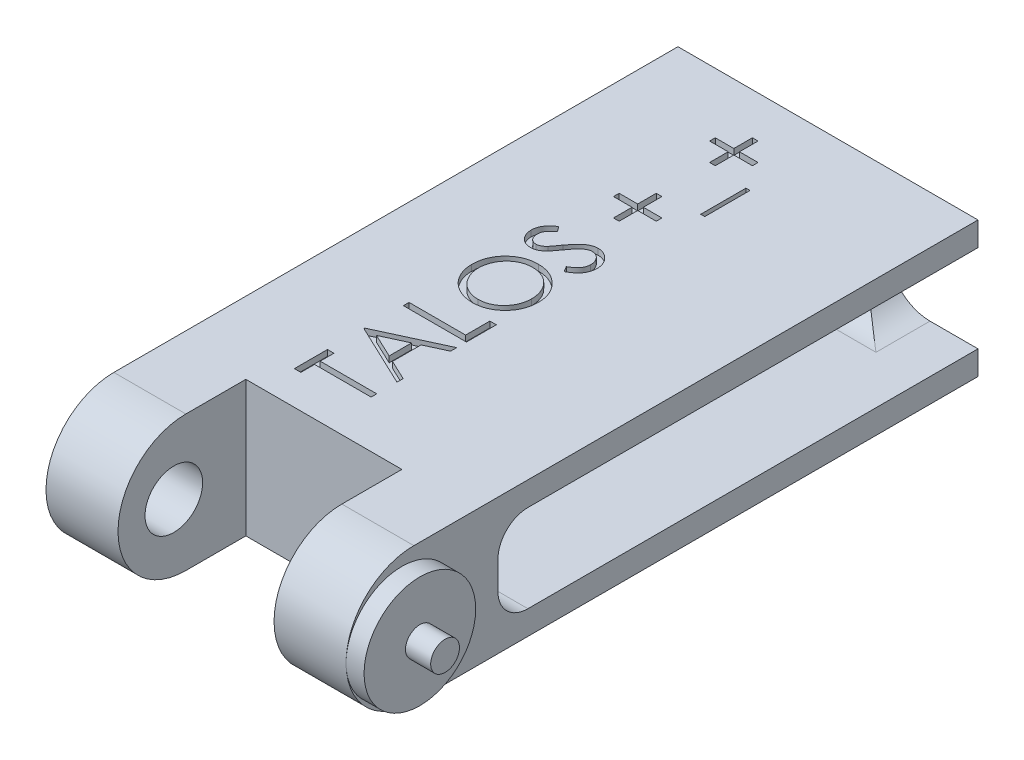
SolidWorks part; units mm, degrees
ref_plane "Front Plane" through (0, 0, 0) normal (0, 0, 1) x (1, 0, 0)
ref_plane "Top Plane" through (0, 0, 0) normal (0, 1, 0) x (1, 0, 0)
ref_plane "Right Plane" through (0, 0, 0) normal (1, 0, 0) x (0, 0, -1)
sketch "Sketch1" plane through (0, 0, 0) normal (0, 0, 1) x (1, 0, 0)
  line L1 (-10, 7.3) -> (10, 7.3)
  line L2 (-10, 7.3) -> (-10, -7.3)
  line L3 (-10, -7.3) -> (10, -7.3)
  line L4 (10, 7.3) -> (10, -7.3)
  line L5 (0, -7.3) -> (0, 7.3) construction
  line L6 (-10, 0) -> (10, 0) construction
  circle A0 centre (-6, 0) radius 1.65
  circle A1 centre (6, 0) radius 1.65
  point P0 (0, 0)
  dimension "D3" = 3.3
  dimension "D4" = 12
  dimension "D1" = 20
  dimension "D2" = 14.6
extrude "Boss-Extrude1" add sketch "Sketch1" along normal blind 4
sketch "Sketch2" plane through (0, -7.3, 0) normal (0, -1, 0) x (1, 0, 0)
  line L0 (-10, 0) -> (10, 0) construction
  line L1 (-25, 0) -> (25, 0)
  line L2 (-25, 0) -> (-25, 80)
  line L3 (-25, 80) -> (25, 80)
  line L4 (25, 0) -> (25, 80)
  point P4 (0, 80)
  point P6 (25, 6.4269)
  dimension "D1" = 50
  dimension "D2" = 80
extrude "Boss-Extrude2" add sketch "Sketch2" along normal blind 4
chamfer "Chamfer1" [suppressed] distance 10 angle 45
mirror "Mirror1" about plane through (0, 0, 0) normal (0, 1, 0) of "Boss-Extrude2"
sketch "Sketch3" plane through (0, 0, 80) normal (0, 0, 1) x (1, 0, 0)
  line L1 (-25, 11.3) -> (25, 11.3)
  line L2 (-25, 11.3) -> (-25, -11.3)
  line L3 (-25, -11.3) -> (25, -11.3)
  line L4 (25, 11.3) -> (25, -11.3)
extrude "Boss-Extrude3" add sketch "Sketch3" along normal blind 4
sketch "Sketch4" plane through (25, 0, 0) normal (1, 0, 0) x (0, 0, -1)
  line L0 (-84, 11.3) -> (-94, 11.3)
  line L1 (-94, -11.3) -> (-84, -11.3)
  line L2 (-84, -11.3) -> (-84, 11.3)
  arc A0 (-94, 11.3) -> (-94, -11.3) centre (-94, 0) ccw
  circle A1 centre (-96, 0) radius 4.8
  point P10 (0, 0)
  point P12 (0, 0)
  dimension "D2" = 9.6
  dimension "D3" = 12
  dimension "D1" = 10
extrude "Boss-Extrude4" add sketch "Sketch4" against normal blind 12
mirror "Mirror2" about plane through (0, 0, 0) normal (1, 0, 0) of "Boss-Extrude4"
sketch "Sketch5" plane through (25, 0, 0) normal (1, 0, 0) x (0, 0, -1)
  circle A0 centre (-96, 0) radius 9.3
  arc A1 (-94, 11.3) -> (-94, -11.3) centre (-94, 0) ccw construction
extrude "Boss-Extrude5" add sketch "Sketch5" along normal blind 3
sketch "Sketch6" plane through (28, 0, 0) normal (1, 0, 0) x (0, 0, -1)
  circle A0 centre (-96, 0) radius 2.4
  dimension "D1" = 4.8
extrude "Boss-Extrude6" add sketch "Sketch6" along normal blind 4.2
fillet "Fillet1" radius 7 4 edges at (-10, -7.3, 2) (-10, 7.3, 2) (10, 7.3, 2) (10, -7.3, 2)
fillet "Fillet2" radius 5 2 edges at (0, 7.3, 4) (0, -7.3, 4)
fillet "Fillet3" radius 5 2 edges at (0, -7.3, 80) (0, 7.3, 80)
sketch "Sketch7" plane through (0, 11.3, 0) normal (0, 1, 0) x (1, 0, 0)
  line L0 (0, -78.5505) -> (0, 0) construction
  line L2 (-25, 0) -> (25, 0) construction
  text T0 "TALOS +_+\r\n" font "Century Gothic" height 10.5
  point P2 (0, -75.0671)
  point P3 (0, -63.9884)
  point P6 (0, -78.5505)
  point P7 (0, -84)
  point P8 (0, -72.2559)
extrude "Cut-Extrude1" cut sketch "Sketch7" against normal blind 1
